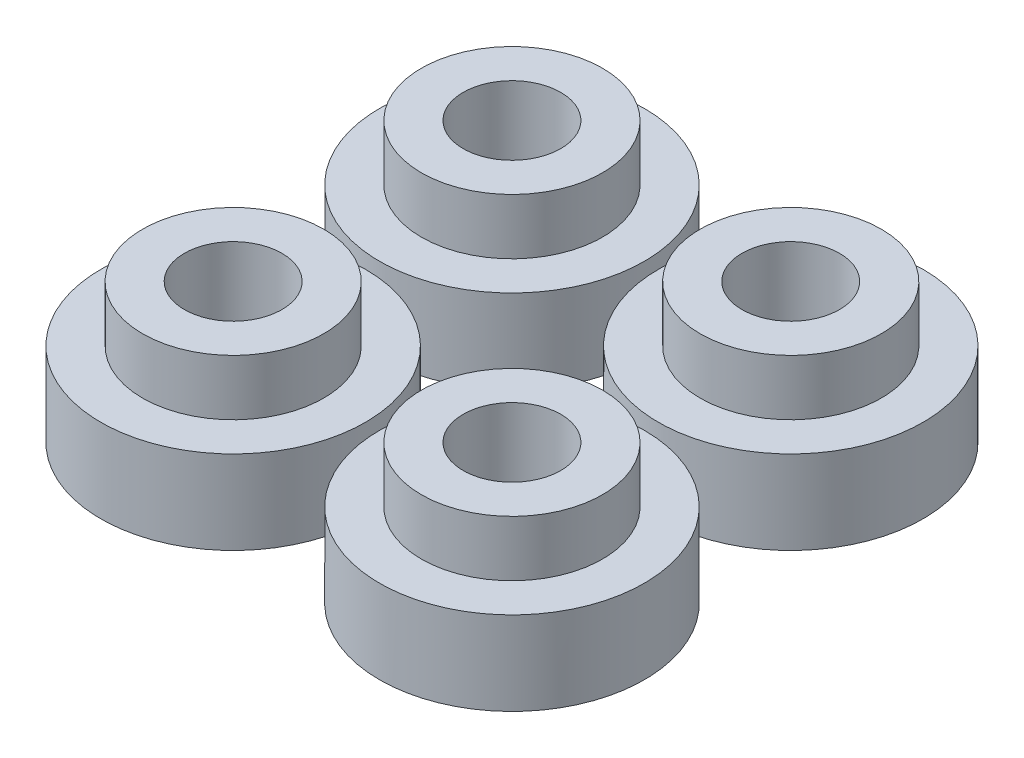
SolidWorks part; units mm, degrees
ref_plane "Front Plane" through (0, 0, 0) normal (0, 0, 1) x (1, 0, 0)
ref_plane "Top Plane" through (0, 0, 0) normal (0, 1, 0) x (1, 0, 0)
ref_plane "Right Plane" through (0, 0, 0) normal (1, 0, 0) x (0, 0, -1)
sketch "Sketch1" plane through (0, 0, 0) normal (0, 0, 1) x (1, 0, 0)
  line L0 (1.75, 0) -> (1.75, 5)
  line L1 (1.75, 5) -> (3.25, 5)
  line L2 (3.25, 5) -> (3.25, 3)
  line L3 (3.25, 3) -> (4.75, 3)
  line L4 (4.75, 3) -> (4.75, 0)
  line L5 (4.75, 0) -> (1.75, 0)
  line L6 (0, 0) -> (0, 67.4038) construction
  dimension "D1" = 3.5
  dimension "D2" = 6.5
  dimension "D3" = 9.5
  dimension "D4" = 5
  dimension "D5" = 3
revolve "Revolve1" add sketch "Sketch1" angle 360 about L6
sketch "Sketch3" plane through (0, 0, 0) normal (0, -1, 0) x (1, 0, 0)
  line L1 (0, 0) -> (10, 0)
  line L2 (0, 0) -> (0, 10)
  line L3 (0, 10) -> (10, 10)
  line L4 (10, 0) -> (10, 10)
  dimension "D1" = 10
extrude "Boss-Extrude1" add sketch "Sketch3" along normal blind 10
pattern_linear "LPattern2" count 2 spacing 10 along (0, 0, 1) count 2 spacing 10 along (1, 0, 0) of "Revolve1"
sketch "Sketch4" plane through (0, -10, 0) normal (0, -1, 0) x (1, 0, 0)
  line L4 (0, 10) -> (0, 0)
  line L5 (0, 0) -> (10, 0)
  line L6 (10, 0) -> (10, 10)
  line L7 (10, 10) -> (0, 10)
  line L8 (0, 10) -> (0, 0)
  line L9 (0, 0) -> (10, 0)
  line L10 (10, 0) -> (10, 10)
  line L11 (10, 10) -> (0, 10)
  dimension "D1" = 0
extrude "Cut-Extrude1" cut sketch "Sketch4" against normal blind 10
